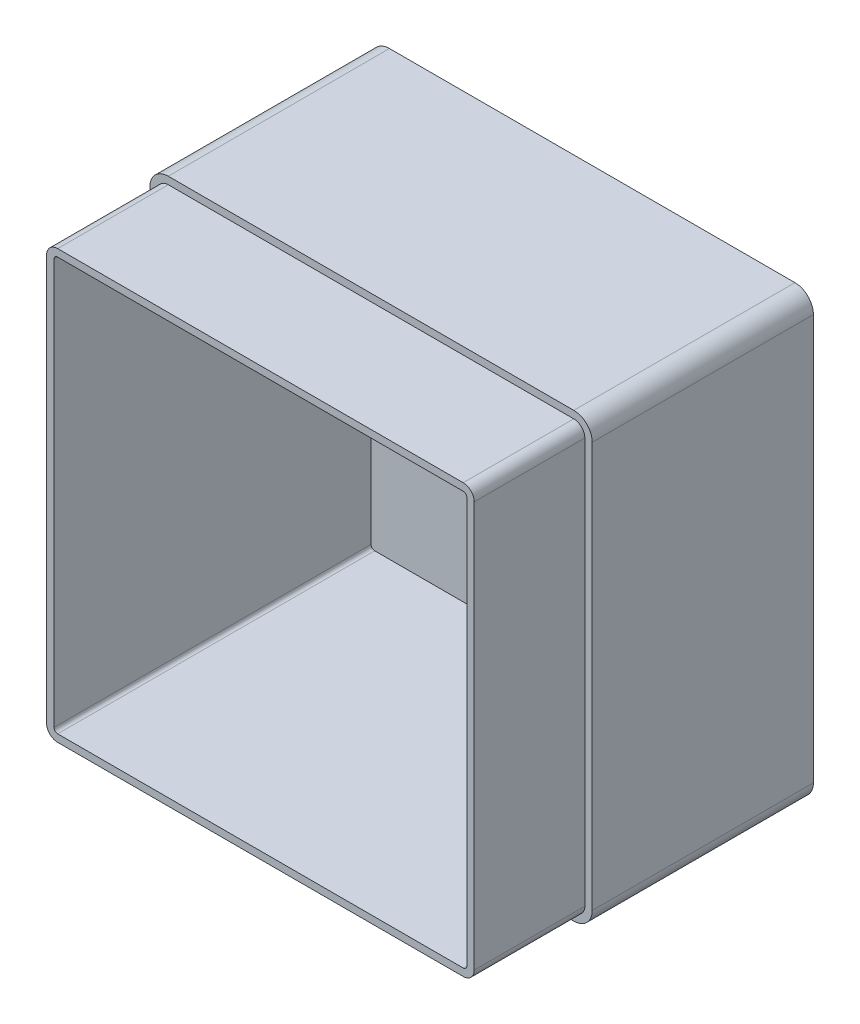
SolidWorks part; units mm, degrees
ref_plane "Front Plane" through (0, 0, 0) normal (0, 0, 1) x (1, 0, 0)
ref_plane "Top Plane" through (0, 0, 0) normal (0, 1, 0) x (1, 0, 0)
ref_plane "Right Plane" through (0, 0, 0) normal (1, 0, 0) x (0, 0, -1)
sketch "Sketch1" plane through (0, 0, 0) normal (0, 0, 1) x (1, 0, 0)
  line L2 (-60, 60) -> (60, 60)
  line L3 (-60, 60) -> (-60, -60)
  line L4 (-60, -60) -> (60, -60)
  line L5 (60, 60) -> (60, -60)
  line L6 (0, -60) -> (0, 60) construction
  line L7 (-60, 0) -> (60, 0) construction
  point P1 (0, 0)
  dimension "D1" = 120
  dimension "D2" = 120
extrude "Boss-Extrude1" add sketch "Sketch1" along normal blind 90
fillet "Fillet1" radius 5 4 edges at (60, -60, 45) (-60, -60, 45) (-60, 60, 45) (60, 60, 45)
shell "Shell1" thickness 4
sketch "Sketch2" plane through (0, 0, 90) normal (0, 0, 1) x (1, 0, 0)
  line L0 (55, 58) -> (-55, 58)
  line L1 (-58, 55) -> (-58, -55)
  line L2 (-55, -58) -> (55, -58)
  line L3 (58, -55) -> (58, 55)
  line L4 (-55, -60) -> (55, -60)
  line L5 (60, -55) -> (60, 55)
  line L6 (55, 60) -> (-55, 60)
  line L7 (-60, 55) -> (-60, -55)
  line L8 (-55, -60) -> (55, -60)
  line L9 (60, -55) -> (60, 55)
  line L10 (55, 60) -> (-55, 60)
  line L11 (-60, 55) -> (-60, -55)
  arc A0 (-55, 58) -> (-58, 55) centre (-55, 55) ccw
  arc A1 (-58, -55) -> (-55, -58) centre (-55, -55) ccw
  arc A2 (55, -58) -> (58, -55) centre (55, -55) ccw
  arc A3 (58, 55) -> (55, 58) centre (55, 55) ccw
  arc A4 (55, -60) -> (60, -55) centre (55, -55) ccw
  arc A5 (60, 55) -> (55, 60) centre (55, 55) ccw
  arc A6 (-55, 60) -> (-60, 55) centre (-55, 55) ccw
  arc A7 (-60, -55) -> (-55, -60) centre (-55, -55) ccw
  arc A8 (55, -60) -> (60, -55) centre (55, -55) ccw
  arc A9 (60, 55) -> (55, 60) centre (55, 55) ccw
  arc A10 (-55, 60) -> (-60, 55) centre (-55, 55) ccw
  arc A11 (-60, -55) -> (-55, -60) centre (-55, -55) ccw
  dimension "D1" = 0
  dimension "D2" = 2
extrude "Cut-Extrude1" cut sketch "Sketch2" against normal blind 30
